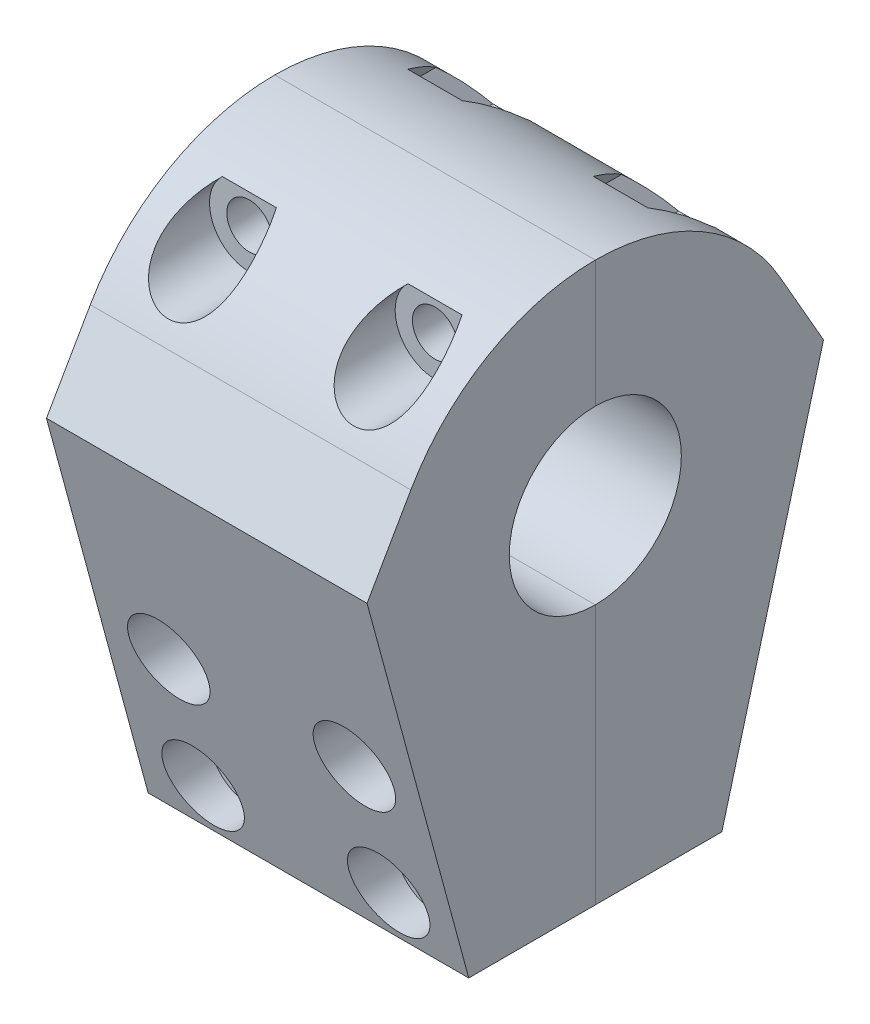
SolidWorks part; units mm, degrees
ref_plane "Front Plane" through (0, 0, 0) normal (0, 0, 1) x (1, 0, 0)
ref_plane "Top Plane" through (0, 0, 0) normal (0, 1, 0) x (1, 0, 0)
ref_plane "Right Plane" through (0, 0, 0) normal (1, 0, 0) x (0, 0, -1)
sketch "Sketch1" plane through (0, 0, 0) normal (0, 1, 0) x (1, 0, 0)
  line L0 (-12.065, 0) -> (12.065, 0) construction
  line L1 (12.065, -9.525) -> (-12.065, -9.525)
  line L2 (12.065, -9.525) -> (12.065, 9.525)
  line L3 (12.065, 9.525) -> (-12.065, 9.525)
  line L4 (-12.065, -9.525) -> (-12.065, 9.525)
  line L5 (12.065, -9.525) -> (-12.065, 9.525) construction
  line L6 (12.065, 9.525) -> (-12.065, -9.525) construction
  line L7 (0, -9.525) -> (0, 9.525) construction
  ellipse E0 centre (0, 0) end of major axis (-3.81, 0) minor radius 3.175
  dimension "D1" = 6.35
  dimension "D2" = 24.13
  dimension "D3" = 19.05
  dimension "D4" = 7.62
extrude "Boss-Extrude1" add sketch "Sketch1" along normal mid plane 16.51 contours L4 L3 L2 L1
ref_plane "Plane1" through (0, 0, 9.525) normal (0, 0, 1) x (1, 0, 0)
ref_plane "Plane2" through (0, 0, -9.525) normal (0, 0, -1) x (-1, 0, 0)
sketch "Sketch18" plane through (-12.065, 0, 0) normal (-1, 0, 0) x (0, 0, 1)
  line L0 (-9.525, 8.255) -> (9.525, 8.255) construction
  line L1 (15.4451, 13.5953) -> (9.525, -8.255)
  line L2 (-15.4451, 13.5953) -> (-9.525, -8.255)
  line L3 (-9.525, 8.255) -> (-9.525, -8.255) construction
  line L4 (-9.525, -8.255) -> (-9.525, 8.255)
  line L5 (-9.525, 8.255) -> (9.525, 8.255)
  line L6 (9.525, 8.255) -> (9.525, -8.255)
  line L7 (-9.525, -8.255) -> (9.525, -8.255) construction
  line L8 (-15.4451, 13.5953) -> (-17.1785, 19.9929)
  line L9 (15.4451, 13.5953) -> (17.1785, 19.9929)
  line L10 (-17.1785, 19.9929) -> (-13.8804, 25.7423)
  line L11 (17.1785, 19.9929) -> (13.8804, 25.7423)
  circle A0 centre (0, 17.78) radius 6.477
  arc A1 (13.8804, 25.7423) -> (-13.8804, 25.7423) centre (0, 17.78) ccw
  arc A2 (-15.4451, 13.5953) -> (15.4451, 13.5953) centre (0, 17.78) ccw construction
  arc A3 (-13.8804, 25.7423) -> (-15.4451, 13.5953) centre (0, 17.78) ccw construction
  arc A4 (15.4451, 13.5953) -> (13.8804, 25.7423) centre (0, 17.78) ccw construction
  dimension "D1" = 12.954
  dimension "D2" = 9.525
  dimension "D3" = 9.525
  dimension "D4" = 45
  dimension "D5" = 45
extrude "Boss-Extrude6" add sketch "Sketch18" against normal up to surface (24.13 mm away) up to face at (12.065, 0, 0)
sketch "Sketch3" plane through (0, 0, 9.525) normal (0, 0, 1) x (1, 0, 0)
  line L1 (6.985, -4.7625) -> (-6.985, -4.7625) construction
  line L2 (6.985, -4.7625) -> (6.985, 4.7625) construction
  line L3 (6.985, 4.7625) -> (-6.985, 4.7625) construction
  line L4 (-6.985, -4.7625) -> (-6.985, 4.7625) construction
  line L5 (6.985, -4.7625) -> (-6.985, 4.7625) construction
  line L6 (6.985, 4.7625) -> (-6.985, -4.7625) construction
  line L7 (-12.065, -8.255) -> (-12.065, 19.9929) construction
  line L8 (-6.985, 29.972) -> (6.985, 29.972) construction
  line L13 (-12.065, 33.782) -> (-12.065, 25.7423) construction
  line L14 (-12.065, 33.782) -> (-12.065, 25.7423) construction
  point P7 (-6.985, 4.7625)
  point P8 (-6.985, -4.7625)
  point P9 (6.985, 4.7625)
  point P10 (6.985, -4.7625)
  point P16 (6.985, 29.972)
  point P18 (-6.985, 29.972)
  dimension "D1" = 5.08
  dimension "D2" = 9.525
  dimension "D3" = 3.81
sketch "Sketch4" plane through (0, 0, 9.525) normal (0, 0, 1) x (1, 0, 0)
  circle A0 centre (-6.985, 4.7625) radius 1.7
  circle A1 centre (-6.985, 4.7625) radius 2.75
  dimension "D1" = 3.4
  dimension "D2" = 5.5
extrude "Cut-Extrude1" cut sketch "Sketch4" against normal through all contours A0
sketch "Sketch13" plane through (0, 0, 9.525) normal (0, 0, 1) x (1, 0, 0)
  circle A0 centre (-6.985, 4.7625) radius 3
  dimension "D1" = 6
extrude "Cut-Extrude4" cut sketch "Sketch13" against normal blind 2.54 and the other way through all
sketch "Sketch19" plane through (0, 0, -9.525) normal (0, 0, -1) x (-1, 0, 0)
  line L1 (10.3048, 4.7625) -> (8.6449, 7.6375)
  line L2 (8.6449, 7.6375) -> (5.3251, 7.6375)
  line L3 (5.3251, 7.6375) -> (3.6652, 4.7625)
  line L4 (3.6652, 4.7625) -> (5.3251, 1.8875)
  line L5 (5.3251, 1.8875) -> (8.6449, 1.8875)
  line L6 (8.6449, 1.8875) -> (10.3048, 4.7625)
  circle A0 centre (6.985, 4.7625) radius 2.875 construction
  dimension "D1" = 5.75
extrude "Cut-Extrude6" cut sketch "Sketch19" against normal blind 2.54 and the other way through all
pattern_sketch "Sketch-Pattern1" of "Cut-Extrude1", "Cut-Extrude4", "Cut-Extrude6" driven by "Sketch3"
sketch "Sketch20" plane through (12.065, 0, 0) normal (1, 0, 0) x (0, 0, -1)
  line L0 (0, -8.255) -> (0, 33.782)
  line L1 (-9.525, -8.255) -> (9.525, -8.255) construction
  arc A0 (13.8804, 25.7423) -> (-13.8804, 25.7423) centre (0, 17.78) ccw construction
  point P3 (0, 0)
  point P6 (0, 0)
split "Split1" trim tools "Sketch20" bodies to split 103 resulting bodies 119 120
equation "\"D1@Sketch13\"=6mm"
equation "\"D1@Sketch19\"=5.75mm"
